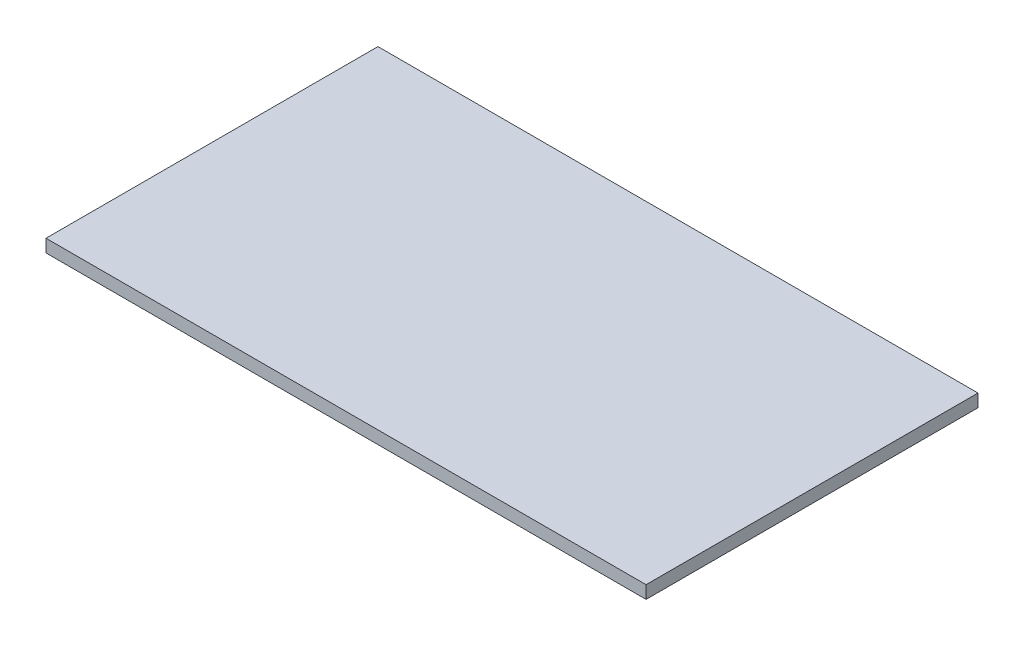
SolidWorks part; units mm, degrees
ref_plane "Front Plane" through (0, 0, 0) normal (0, 0, 1) x (1, 0, 0)
ref_plane "Top Plane" through (0, 0, 0) normal (0, 1, 0) x (1, 0, 0)
ref_plane "Right Plane" through (0, 0, 0) normal (1, 0, 0) x (0, 0, -1)
sketch "Sketch1" plane through (0, 0, 0) normal (0, 1, 0) x (1, 0, 0)
  line L1 (-149.225, -82.55) -> (149.225, -82.55)
  line L2 (-149.225, -82.55) -> (-149.225, 82.55)
  line L3 (-149.225, 82.55) -> (149.225, 82.55)
  line L4 (149.225, -82.55) -> (149.225, 82.55)
  line L5 (-149.225, -82.55) -> (149.225, 82.55) construction
  line L6 (-149.225, 82.55) -> (149.225, -82.55) construction
  point P0 (0, 0)
  dimension "D1" = 298.45
  dimension "D2" = 165.1
extrude "Boss-Extrude1" add sketch "Sketch1" along normal blind 6.35
equation "\"base-width\"= \"box-inner-width\" + 2 * \"material-thickness\""
equation "\"box-inner-width\"= 6in"
equation "\"material-thickness\"= 0.25in"
equation "\"converter-cell-inner-length\"= 9in"
equation "\"bus-bar-cell-inner-length\"= 2.5in"
equation "\"base-length\"= \"converter-cell-inner-length\" + \"bus-bar-cell-inner-length\" + \"material-thickness\""
equation "\"D1@Boss-Extrude1\"=\"material-thickness\""
equation "\"D1@Sketch1\"=\"base-length\""
equation "\"D2@Sketch1\"=\"base-width\""
